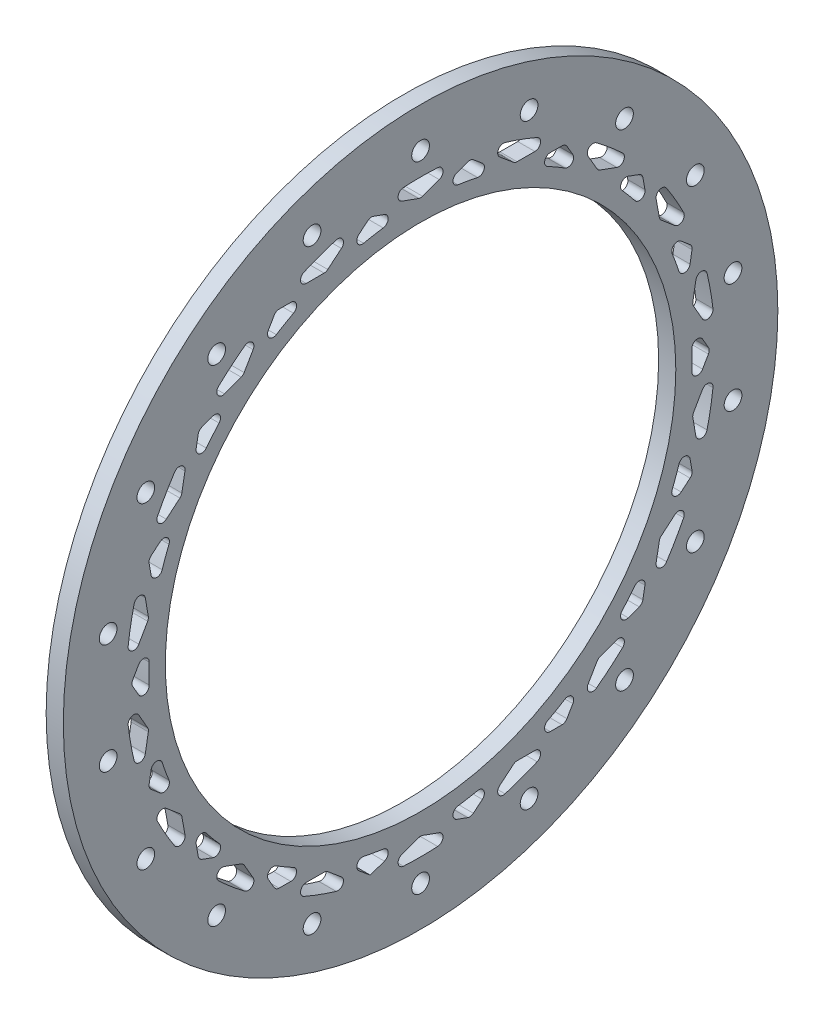
SolidWorks part; units mm, degrees
ref_plane "前视基准面" through (0, 0, 0) normal (0, 0, 1) x (1, 0, 0)
ref_plane "上视基准面" through (0, 0, 0) normal (0, 1, 0) x (1, 0, 0)
ref_plane "右视基准面" through (0, 0, 0) normal (1, 0, 0) x (0, 0, -1)
other "Configuration Table"
sketch "草图1" plane through (0, 0, 0) normal (1, 0, 0) x (0, 0, -1)
  circle A0 centre (0, 0) radius 44.65
  circle A1 centre (0, 0) radius 62.5
  dimension "D1" = 125
  dimension "D2" = 89.3
extrude "凸台-拉伸1" add sketch "草图1" along normal blind 3
sketch "草图2" plane through (3, 0, 0) normal (1, 0, 0) x (0, 0, -1)
  circle A0 centre (0, 55.5) radius 1.55
  dimension "D2" = 3.1
  dimension "D1" = 55.5
extrude "切除-拉伸1" cut sketch "草图2" against normal through all
pattern_circular "阵列(圆周)1" count 18 every 20 about axis through (0, 0, 0) along (1, 0, 0) of "切除-拉伸1"
sketch "草图3" plane through (3, 0, 0) normal (1, 0, 0) x (0, 0, -1)
  circle A0 centre (0, 0) radius 51.5
  circle A1 centre (0, 0) radius 47.5
  dimension "D1" = 95
  dimension "D2" = 103
extrude "切除-拉伸2" cut sketch "草图3" against normal through all
sketch "草图4" plane through (3, 0, 0) normal (1, 0, 0) x (0, 0, -1)
  line L1 (0, 47.5) -> (8.9429, 50.7176)
  line L4 (8.9429, 50.7176) -> (16.246, 44.6354)
  line L5 (0, 47.5) -> (0, 0) construction
  line L6 (0, 0) -> (8.9429, 50.7176) construction
  line L7 (16.246, 44.6354) -> (0, 0) construction
  line L8 (25.75, 44.6003) -> (30.5324, 36.3871)
  line L9 (16.246, 44.6354) -> (25.75, 44.6003)
  line L10 (39.4513, 33.1036) -> (41.1362, 23.75)
  line L11 (30.5324, 36.3871) -> (39.4513, 33.1036)
  line L12 (48.3942, 17.614) -> (46.7784, 8.2483)
  line L13 (41.1362, 23.75) -> (48.3942, 17.614)
  line L14 (51.5, 0) -> (46.7784, -8.2483)
  line L15 (46.7784, 8.2483) -> (51.5, 0)
  line L16 (48.3942, -17.614) -> (41.1362, -23.75)
  line L17 (46.7784, -8.2483) -> (48.3942, -17.614)
  line L18 (39.4513, -33.1036) -> (30.5324, -36.3871)
  line L19 (41.1362, -23.75) -> (39.4513, -33.1036)
  line L20 (25.75, -44.6003) -> (16.246, -44.6354)
  line L21 (30.5324, -36.3871) -> (25.75, -44.6003)
  line L22 (8.9429, -50.7176) -> (0, -47.5)
  line L23 (16.246, -44.6354) -> (8.9429, -50.7176)
  line L24 (-8.9429, -50.7176) -> (-16.246, -44.6354)
  line L25 (0, -47.5) -> (-8.9429, -50.7176)
  line L26 (-25.75, -44.6003) -> (-30.5324, -36.3871)
  line L27 (-16.246, -44.6354) -> (-25.75, -44.6003)
  line L28 (-39.4513, -33.1036) -> (-41.1362, -23.75)
  line L29 (-30.5324, -36.3871) -> (-39.4513, -33.1036)
  line L30 (-48.3942, -17.614) -> (-46.7784, -8.2483)
  line L31 (-41.1362, -23.75) -> (-48.3942, -17.614)
  line L32 (-51.5, 0) -> (-46.7784, 8.2483)
  line L33 (-46.7784, -8.2483) -> (-51.5, 0)
  line L34 (-48.3942, 17.614) -> (-41.1362, 23.75)
  line L35 (-46.7784, 8.2483) -> (-48.3942, 17.614)
  line L36 (-39.4513, 33.1036) -> (-30.5324, 36.3871)
  line L37 (-41.1362, 23.75) -> (-39.4513, 33.1036)
  line L38 (-25.75, 44.6003) -> (-16.246, 44.6354)
  line L39 (-30.5324, 36.3871) -> (-25.75, 44.6003)
  line L40 (-8.9429, 50.7176) -> (0, 47.5)
  line L41 (-16.246, 44.6354) -> (-8.9429, 50.7176)
  circle A3 centre (0, 0) radius 47.5 construction
  circle A4 centre (0, 0) radius 51.5 construction
  point P63 (0, 0)
  dimension "D3" = 18
  dimension "D1" = 10
  dimension "D2" = 10
extrude "拉伸-薄壁4" add sketch "草图4" against normal through all thin thin type mid plane wall 1.5
fillet "圆角1" radius 1 93 edges at (1.5, 49.8665, 8.7928) (1.5, 47.4541, 2.0878) (1.5, 45.3063, -14.2684) (1.5, 49.8665, -8.7928) (1.5, 48.2971, 0) (1.5, 50.9638, -7.4119) (1.5, 50.9638, 7.4119) (1.5, 45.3844, -16.5186) (1.5, 45.3553, -24.3956) (1.5, 50.4254, -10.4657) (1.5, 43.8049, -27.0811) (1.5, 36.9977, -31.0448) (1.5, 32.5481, -38.7893) (1.5, 35.01, -32.1022) (1.5, 25.5351, -40.0526) (1.5, 19.063, -47.842) (1.5, 24.1485, -41.8265) (1.5, 21.919, -42.1403) (1.5, 10.2964, -46.3706) (1.5, 17.3185, -47.5821) (1.5, 31.9008, -40.43) (1.5, 16.1491, -48.9025) (1.5, 8.3867, -47.5633) (1.5, 1.5504, -51.4767) (1.5, -16.1491, -48.9025) (1.5, -1.5504, -51.4767) (1.5, -6.1843, -47.0957) (1.5, 0, -50.6358) (1.5, 6.1843, -47.0957) (1.5, -10.2964, -46.3706) (1.5, -17.3185, -47.5821) (1.5, -19.063, -47.842) (1.5, -31.9008, -40.43) (1.5, -24.1485, -41.8265) (1.5, -35.01, -32.1022) (1.5, -25.5351, -40.0526) (1.5, -32.5481, -38.7893) (1.5, -43.8049, -27.0811) (1.5, -34.2763, -38.4368) (1.5, -36.9977, -31.0448) (1.5, -43.8782, -18.1921) (1.5, -37.6939, -28.9036) (1.5, -43.8519, -25.3179) (1.5, -50.4254, -10.4657) (1.5, -45.3553, -24.3956) (1.5, -45.3844, -16.5186) (1.5, -47.4541, -2.0878) (1.5, -49.8665, -8.7928) (1.5, -50.9638, -7.4119) (1.5, -48.2971, 0) (1.5, -47.4541, 2.0878) (1.5, -43.8519, 25.3179) (1.5, -50.9638, 7.4119) (1.5, -45.3844, 16.5186) (1.5, -45.3063, 14.2684) (1.5, -37.6939, 28.9036) (1.5, -50.4254, 10.4657) (1.5, -43.8049, 27.0811) (1.5, -34.2763, 38.4368) (1.5, -36.9977, 31.0448) (1.5, -32.5481, 38.7893) (1.5, -35.01, 32.1022) (1.5, -25.5351, 40.0526) (1.5, -21.919, 42.1403) (1.5, -10.2964, 46.3706) (1.5, -17.3185, 47.5821) (1.5, -31.9008, 40.43) (1.5, -19.063, 47.842) (1.5, -1.5504, 51.4767) (1.5, -8.3867, 47.5633) (1.5, -6.1843, 47.0957) (1.5, 6.1843, 47.0957) (1.5, 0, 50.6358) (1.5, 1.5504, 51.4767) (1.5, 16.1491, 48.9025) (1.5, 8.3867, 47.5633) (1.5, 21.919, 42.1403) (1.5, 17.3185, 47.5821) (1.5, 19.063, 47.842) (1.5, 31.9008, 40.43) (1.5, 24.1485, 41.8265) (1.5, 35.01, 32.1022) (1.5, 32.5481, 38.7893) (1.5, 36.9977, 31.0448) (1.5, 43.8049, 27.0811) (1.5, 34.2763, 38.4368) (1.5, 43.8519, 25.3179) (1.5, 43.8782, 18.1921) (1.5, 45.3553, 24.3956) (1.5, 50.4254, 10.4657) (1.5, 37.6939, -28.9036) (1.5, 43.8782, -18.1921) (1.5, 43.8519, -25.3179)
